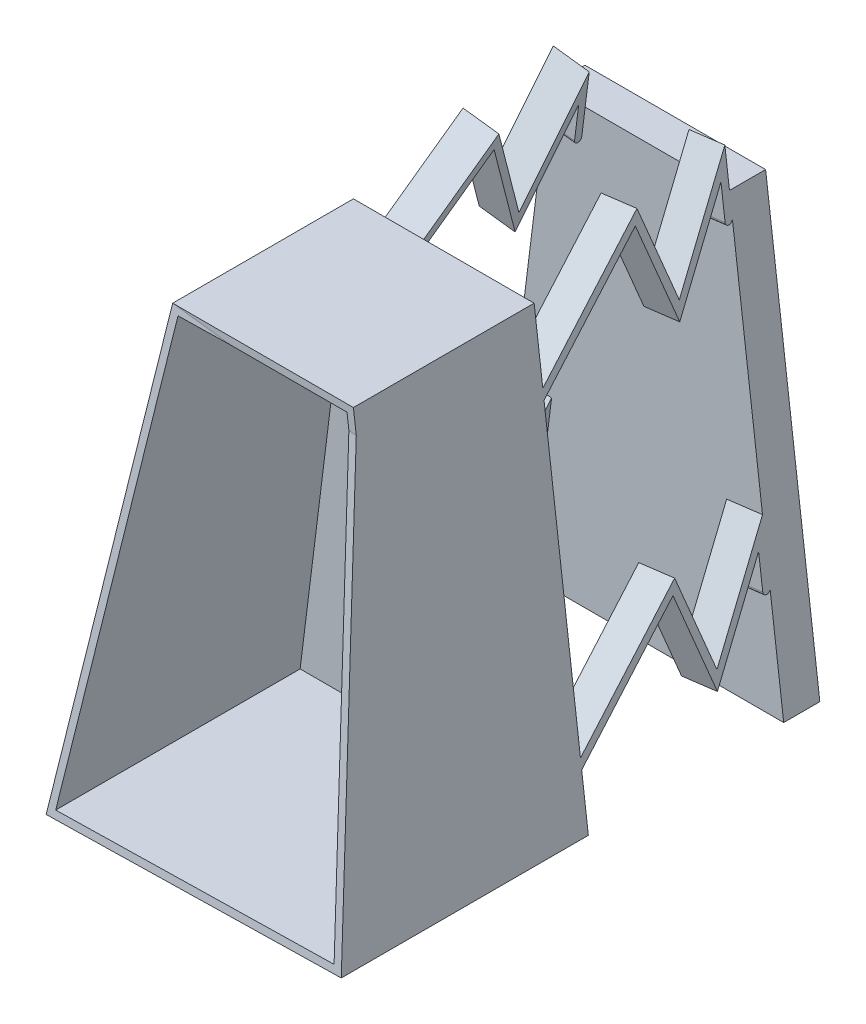
SolidWorks part; units mm, degrees
ref_plane "Front Plane" through (0, 0, 0) normal (0, 0, 1) x (1, 0, 0)
ref_plane "Top Plane" through (0, 0, 0) normal (0, 1, 0) x (1, 0, 0)
ref_plane "Right Plane" through (0, 0, 0) normal (1, 0, 0) x (0, 0, -1)
sketch "Sketch1" plane through (0, 0, 0) normal (0, 0, 1) x (1, 0, 0)
  line L0 (-125, 424.3355) -> (125, 424.3355)
  line L1 (-200, -175.6645) -> (200, -175.6645)
  line L2 (-125, 424.3355) -> (-200, -175.6645)
  line L3 (125, 424.3355) -> (200, -175.6645)
  point P4 (0, 424.3355)
  point P5 (0, -175.6645)
  dimension "D1" = 250
  dimension "D2" = 400
  dimension "D3" = 600
extrude "Boss-Extrude1" add sketch "Sketch1" along normal blind 350
shell "Shell1" thickness 10
sketch "Sketch2" plane through (-175.3028, 21.9129, 0) normal (-0.9923, 0.124, 0) x (0, 0, 1)
  line L1 (350, 405.5544) -> (0, 405.5544) construction
  line L2 (250, 405.5544) -> (350, -199.1149)
  line L3 (250, 405.5544) -> (350, 405.5544)
  line L4 (350, 405.5544) -> (350, -199.1149)
extrude "Cut-Extrude1" cut sketch "Sketch2" against normal blind 436
sketch "Sketch3" plane through (-175.3028, 21.9129, 0) normal (-0.9923, 0.124, 0) x (0, 0, 1)
  line L1 (250, 405.5544) -> (509.761, 405.5544)
  line L2 (250, 405.5544) -> (250, 501.9645)
  line L3 (250, 501.9645) -> (509.761, 501.9645)
  line L4 (509.761, 405.5544) -> (509.761, 501.9645)
extrude "Cut-Extrude2" cut sketch "Sketch3" against normal through all
sketch "Sketch5" plane through (-175.3028, 21.9129, 0) normal (-0.9923, 0.124, 0) x (0, 0, 1)
  line L0 (0, -124.7449) -> (-142.4672, 5.816)
  line L1 (0, 405.5544) -> (0, -199.1149) construction
  line L2 (-142.4672, 5.816) -> (-187.7516, -124.7449)
  line L3 (-187.7516, -124.7449) -> (-260.2066, 0)
  line L4 (-260.2066, 0) -> (-260.2066, -46.21)
  line L5 (0, 295.2551) -> (-142.4672, 425.816)
  line L6 (-142.4672, 425.816) -> (-187.7516, 295.2551)
  line L7 (-187.7516, 295.2551) -> (-260.2066, 420)
  line L8 (-260.2066, 420) -> (-260.2066, 373.79)
  line L9 (6.7563, 302.6275) -> (-146.9288, 443.4689)
  line L10 (-146.9288, 443.4689) -> (-190.0548, 319.1308)
  line L11 (-190.0548, 319.1308) -> (-270.2066, 457.1272)
  line L12 (-270.2066, 457.1272) -> (-270.2066, 373.79)
  line L13 (6.7563, -117.3725) -> (-146.9288, 23.4689)
  line L14 (-146.9288, 23.4689) -> (-190.0548, -100.8692)
  line L15 (-190.0548, -100.8692) -> (-270.2066, 37.1272)
  line L16 (-270.2066, 37.1272) -> (-270.2066, -46.21)
  arc A0 (0, 295.2551) -> (6.7563, 302.6275) centre (3.3781, 298.9413) ccw
  arc A1 (-260.2066, 373.79) -> (-270.2066, 373.79) centre (-265.2066, 373.79) cw
  arc A2 (0, -124.7449) -> (6.7563, -117.3725) centre (3.3781, -121.0587) ccw
  arc A3 (-260.2066, -46.21) -> (-270.2066, -46.21) centre (-265.2066, -46.21) cw
  dimension "D2" = 10
  dimension "D3" = 10
  dimension "D1" = 2
extrude "Boss-Extrude2" add sketch "Sketch5" against normal blind 50
mirror "Mirror1" about plane through (0, 0, 0) normal (1, 0, 0) of "Boss-Extrude2"
sketch "Sketch6" plane through (0, 0, -270.2066) normal (0, 0, -1) x (-1, 0, 0)
  line L0 (-200, -175.6645) -> (-125, 424.3355)
  line L3 (-200, -175.6645) -> (200, -175.6645)
  line L5 (-125, 424.3355) -> (125, 424.3355)
  line L6 (125, 424.3355) -> (200, -175.6645)
  point P4 (0, -175.6645)
extrude "Boss-Extrude3" add sketch "Sketch6" along normal blind 50
sketch "Sketch7" plane through (0, 0, -320.2066) normal (0, 0, -1) x (-1, 0, 0)
  line L0 (-192.9728, -170.053) -> (-114.8861, 414.2506)
  line L7 (190.2801, -170.053) -> (-192.9728, -170.053)
  line L9 (-114.8861, 414.2506) -> (113.9886, 414.2506)
  line L10 (113.9886, 414.2506) -> (190.2801, -170.053)
extrude "Cut-Extrude3" cut sketch "Sketch7" against normal blind 49
